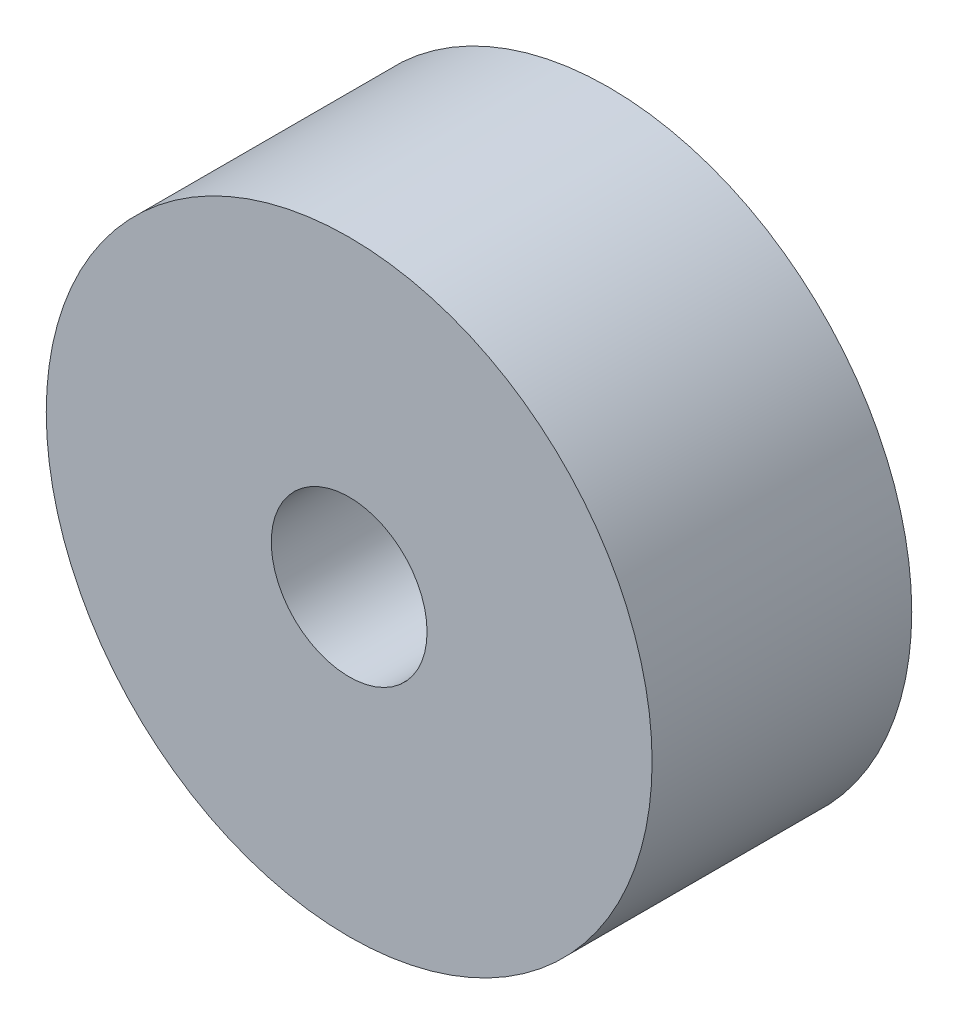
SolidWorks part; units mm, degrees
material "A286 Iron Base Superalloy"
ref_plane "Front Plane" through (0, 0, 0) normal (0, 0, 1) x (1, 0, 0)
ref_plane "Top Plane" through (0, 0, 0) normal (0, 1, 0) x (1, 0, 0)
ref_plane "Right Plane" through (0, 0, 0) normal (1, 0, 0) x (0, 0, -1)
sketch "Sketch1" plane through (0, 0, 0) normal (0, 0, 1) x (1, 0, 0)
  circle A0 centre (0, 0) radius 350
  circle A1 centre (0, 0) radius 90
  dimension "D1" = 700
  dimension "D2" = 180
extrude "Boss-Extrude1" add sketch "Sketch1" along normal blind 300
shell "Shell1" thickness 5
